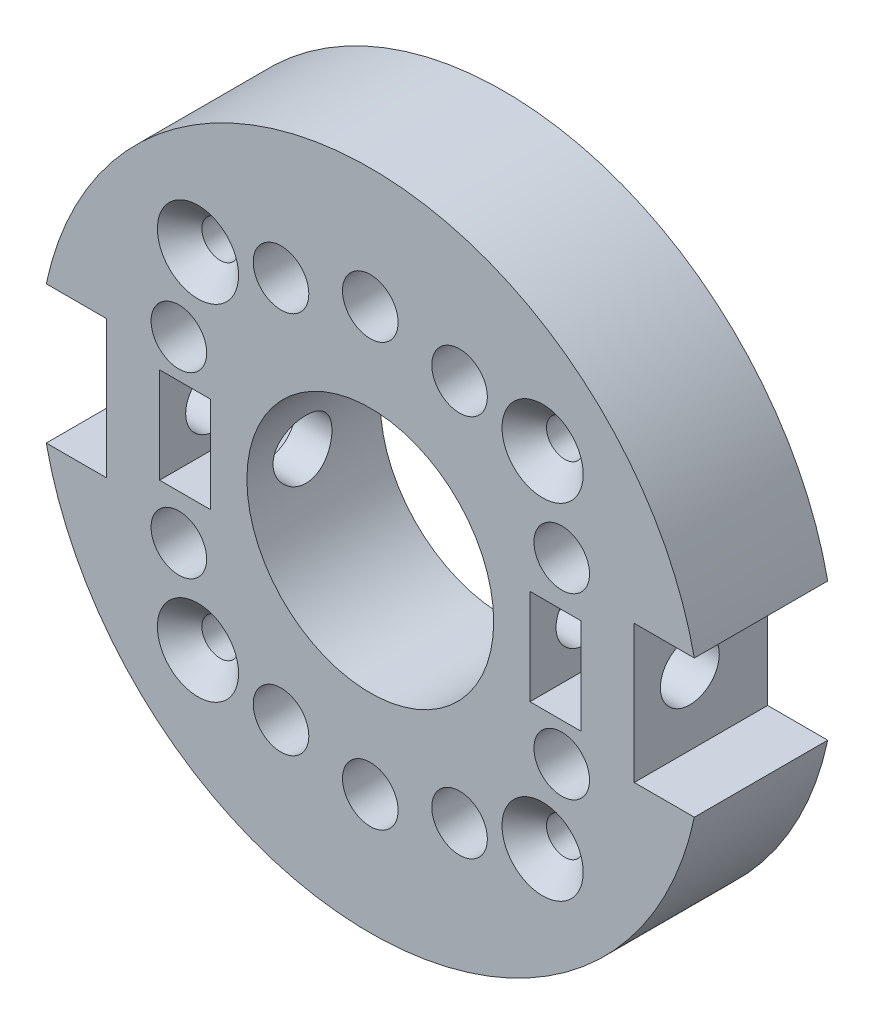
SolidWorks part; units mm, degrees
ref_plane "Plan de face" through (0, 0, 0) normal (0, 0, 1) x (1, 0, 0)
ref_plane "Plan de dessus" through (0, 0, 0) normal (0, 1, 0) x (1, 0, 0)
ref_plane "Plan de droite" through (0, 0, 0) normal (1, 0, 0) x (0, 0, -1)
sketch "Esquisse1" plane through (0, 0, 0) normal (0, 0, 1) x (1, 0, 0)
  line L36 (-18.9562, 4.6) -> (-14.3562, 4.6)
  line L52 (-0.2997, 0.2997) -> (-35355.6388, 35355.6388) construction
  line L54 (0, -1000) -> (0, 49000) construction
  line L60 (23.9414, -6) -> (29.3939, -6) construction
  line L61 (-14.3562, -4) -> (-14.3562, 4.6)
  line L62 (-18.6562, -3.7) -> (-14.6562, -3.7) construction
  line L63 (-18.6562, -3.7) -> (-18.6562, 4.3) construction
  line L64 (-18.6562, 4.3) -> (-14.6562, 4.3) construction
  line L65 (-14.6562, -3.7) -> (-14.6562, 4.3) construction
  line L66 (-18.6562, -3.7) -> (-14.6562, 4.3) construction
  line L67 (-23.9414, -6) -> (-29.3939, -6) construction
  line L68 (-23.9414, -6) -> (-23.9414, 6) construction
  line L69 (-23.9414, 6) -> (-29.3939, 6) construction
  line L71 (23.9414, 6) -> (23.9414, -6) construction
  line L72 (23.9414, 6) -> (29.3939, 6)
  line L73 (-4.2406, 9.094) -> (-21135.1537, 45324.4833) construction
  line L74 (-23.7414, -6.2) -> (-23.7414, 6.2)
  line L75 (-23.7414, 6.2) -> (-29.1479, 6.2)
  line L76 (23.7414, 6.2) -> (29.1479, 6.2)
  line L77 (-18.6562, 4.3) -> (-14.6562, -3.7) construction
  line L78 (-18.9562, -4) -> (-14.3562, -4)
  line L79 (-18.9562, -4) -> (-18.9562, 4.6)
  line L98 (23.7414, 6.2) -> (23.7414, -6.2)
  line L99 (23.7414, -6.2) -> (29.1479, -6.2)
  line L100 (23.7414, 6.2) -> (29.1479, 6.2)
  line L101 (23.7414, 6.2) -> (23.7414, -6.2)
  line L102 (23.7414, -6.2) -> (29.1479, -6.2)
  line L106 (-23.7414, -6.2) -> (-29.1479, -6.2)
  line L107 (6, -23.9414) -> (6, -29.3939) construction
  line L108 (6, -23.9414) -> (-6, -23.9414) construction
  line L109 (-6, -23.9414) -> (-6, -29.3939) construction
  line L110 (23.9414, 6) -> (29.3939, 6) construction
  line L111 (23.9414, 6) -> (23.9414, -6) construction
  line L112 (23.9414, -6) -> (29.3939, -6) construction
  line L113 (18.9562, -4.6) -> (14.3562, -4.6)
  line L114 (14.3562, 4) -> (14.3562, -4.6)
  line L115 (18.9562, 4) -> (14.3562, 4)
  line L116 (18.9562, 4) -> (18.9562, -4.6)
  line L119 (6.2, -23.7414) -> (-6.2, -23.7414) construction
  line L120 (6.2, -23.7414) -> (6.2, -29.1479) construction
  line L121 (-6.2, -23.7414) -> (-6.2, -29.1479) construction
  circle A1 centre (0, 0) radius 11.1
  circle A2 centre (-15.5, 15.5) radius 1.65
  circle A3 centre (15.5, 15.5) radius 1.65
  circle A4 centre (15.5, -15.5) radius 1.65
  circle A5 centre (-15.5, -15.5) radius 1.65
  arc A18 (-29.3939, -6) -> (-6, -29.3939) centre (0, 0) ccw construction
  circle A21 centre (-8.0297, 17.2198) radius 2.5
  arc A23 (29.3939, 6) -> (-29.3939, 6) centre (0, 0) ccw construction
  arc A24 (29.3939, 6) -> (29.3939, -6) centre (0, 0) ccw construction
  arc A25 (6, -29.3939) -> (29.3939, -6) centre (0, 0) ccw construction
  circle A26 centre (8.0297, 17.2198) radius 2.5
  circle A27 centre (17.2198, 8.0297) radius 2.5
  circle A28 centre (17.2198, -8.0297) radius 2.5
  circle A29 centre (8.0297, -17.2198) radius 2.5
  circle A30 centre (-8.0297, -17.2198) radius 2.5
  circle A31 centre (-17.2198, -8.0297) radius 2.5
  circle A32 centre (-17.2198, 8.0297) radius 2.5
  arc A33 (29.1479, 6.2) -> (-29.1479, 6.2) centre (0, 0) ccw
  arc A34 (29.1479, 6.2) -> (29.1479, -6.2) centre (0, 0) ccw
  arc A35 (6.2, -29.1479) -> (29.1479, -6.2) centre (0, 0) ccw
  arc A36 (-29.1479, -6.2) -> (-6.2, -29.1479) centre (0, 0) ccw
  circle A37 centre (0, 19) radius 2.5
  circle A38 centre (0, -19) radius 2.5
  point P1 (-27.9414, 0)
  point P22 (0, 0)
  point P32 (0, 0)
  point P33 (0, 0)
  point P39 (-16.6562, 0.3)
  point P55 (0, 0)
  point P59 (0, 0)
  point P73 (0, 0)
  point P75 (0, 0)
  point P90 (0, 0)
  dimension "D2" = 22.2
  dimension "D7" = 3.3
  dimension "D14" = 0.2
  dimension "D18" = 8
  dimension "D6" = 5.4525
  dimension "D15" = 5
  dimension "D4" = 60
  dimension "D11" = 2
  dimension "D20" = 5
  dimension "D3" = 12
  dimension "D5" = 21.9203
  dimension "D9" = 0.3
  dimension "D10" = 2
  dimension "D16" = 45
  dimension "D17" = 19
  dimension "D19" = 4
  dimension "D12" = 25
  dimension "D21" = 19
  dimension "D8" = 4
  dimension "D13" = 4
  dimension "D22" = 2
extrude "Boss.-Extru.1" add sketch "Esquisse1" along normal blind 12
chamfer "Chanfrein1" distance 2 angle 45 4 edges at (-13.85, -15.5, 12) (17.15, -15.5, 12) (17.15, 15.5, 12) (-13.85, 15.5, 12)
sketch "Esquisse2" plane through (-14.3562, 0, 0) normal (-1, 0, 0) x (0, 0, 1)
  line L1 (12, -6.2) -> (12, 6.2) construction
  circle A0 centre (7, 0) radius 2.65
  dimension "D1" = 5.3
  dimension "D2" = 5
extrude "Enlèv. mat.-Extru.1" cut sketch "Esquisse2" against normal up to next and the other way through all
pattern_circular "Répétition circulaire1" count 2 over 360 about axis through (0, 0, 7) along (1, 0, 0) of "Enlèv. mat.-Extru.1"
sketch "Esquisse4" plane through (0, 0, 0) normal (0, 0, -1) x (-1, 0, 0)
  line L1 (0, 14.3812) -> (4, 16.6906)
  line L2 (4, 16.6906) -> (4, 21.3094)
  line L3 (4, 21.3094) -> (0, 23.6188)
  line L4 (0, 23.6188) -> (-4, 21.3094)
  line L5 (-4, 21.3094) -> (-4, 16.6906)
  line L6 (-4, 16.6906) -> (0, 14.3812)
  line L8 (0, -14.3812) -> (-4, -16.6906)
  line L9 (-4, -16.6906) -> (-4, -21.3094)
  line L10 (-4, -21.3094) -> (0, -23.6188)
  line L11 (0, -23.6188) -> (4, -21.3094)
  line L12 (4, -21.3094) -> (4, -16.6906)
  line L13 (4, -16.6906) -> (0, -14.3812)
  circle A0 centre (0, 19) radius 4 construction
  point P17 (0, 0)
  dimension "D1" = 8
  dimension "D2" = 2
extrude "Enlèv. mat.-Extru.3" cut sketch "Esquisse4" against normal blind 8
